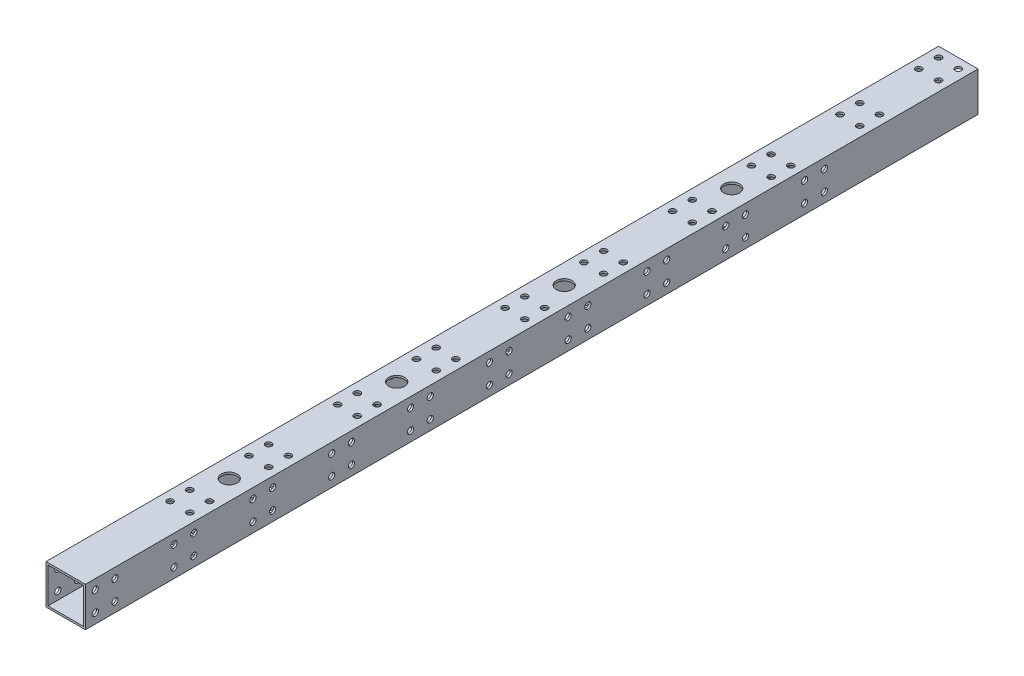
SolidWorks part; units mm, degrees
ref_plane "前视基准面" through (0, 0, 0) normal (0, 0, 1) x (1, 0, 0)
ref_plane "上视基准面" through (0, 0, 0) normal (0, 1, 0) x (1, 0, 0)
ref_plane "右视基准面" through (0, 0, 0) normal (1, 0, 0) x (0, 0, -1)
other "Configuration Table"
sketch "草图1" plane through (0, 0, 0) normal (0, 0, 1) x (1, 0, 0)
  line L1 (0, 0) -> (20, 0)
  line L2 (0, 0) -> (0, -20)
  line L3 (0, -20) -> (20, -20)
  line L4 (20, 0) -> (20, -20)
  dimension "D1" = 20
  dimension "D2" = 20
extrude "拉伸-薄壁1" add sketch "草图1" along normal blind 453 thin
sketch "草图2" plane through (20, 0, 0) normal (1, 0, 0) x (0, 0, -1)
  line L0 (-443, 0) -> (-443, -20) construction
  line L1 (-453, 0) -> (0, 0) construction
  line L2 (-453, -20) -> (0, -20) construction
  line L3 (-453, -20) -> (-453, 0) construction
  line L4 (-453, -10) -> (-443, -10) construction
  circle A0 centre (-448, -5) radius 1.575
  circle A1 centre (-448, -15) radius 1.575
  circle A2 centre (-438, -15) radius 1.575
  circle A3 centre (-438, -5) radius 1.575
  circle A4 centre (-408, -5) radius 1.575
  circle A5 centre (-398, -5) radius 1.575
  circle A6 centre (-398, -15) radius 1.575
  circle A7 centre (-408, -15) radius 1.575
  circle A8 centre (-368, -5) radius 1.575
  circle A9 centre (-358, -5) radius 1.575
  circle A10 centre (-358, -15) radius 1.575
  circle A11 centre (-368, -15) radius 1.575
  circle A12 centre (-328, -5) radius 1.575
  circle A13 centre (-318, -5) radius 1.575
  circle A14 centre (-318, -15) radius 1.575
  circle A15 centre (-328, -15) radius 1.575
  circle A16 centre (-288, -5) radius 1.575
  circle A17 centre (-278, -5) radius 1.575
  circle A18 centre (-278, -15) radius 1.575
  circle A19 centre (-288, -15) radius 1.575
  circle A20 centre (-248, -5) radius 1.575
  circle A21 centre (-238, -5) radius 1.575
  circle A22 centre (-238, -15) radius 1.575
  circle A23 centre (-248, -15) radius 1.575
  circle A24 centre (-208, -5) radius 1.575
  circle A25 centre (-198, -5) radius 1.575
  circle A26 centre (-198, -15) radius 1.575
  circle A27 centre (-208, -15) radius 1.575
  circle A28 centre (-168, -5) radius 1.575
  circle A29 centre (-158, -5) radius 1.575
  circle A30 centre (-158, -15) radius 1.575
  circle A31 centre (-168, -15) radius 1.575
  circle A32 centre (-128, -5) radius 1.575
  circle A33 centre (-118, -5) radius 1.575
  circle A34 centre (-118, -15) radius 1.575
  circle A35 centre (-128, -15) radius 1.575
  circle A36 centre (-88, -5) radius 1.575
  circle A37 centre (-78, -5) radius 1.575
  circle A38 centre (-78, -15) radius 1.575
  circle A39 centre (-88, -15) radius 1.575
  dimension "D1" = 3.15
  dimension "D2" = 10
  dimension "D3" = 5
  dimension "D4" = 5
  dimension "D5" = 40
extrude "切除-拉伸1" cut sketch "草图2" against normal through all
sketch "草图4" plane through (0, -20, 0) normal (0, -1, 0) x (1, 0, 0)
  line L0 (10, 0) -> (10, 10) construction
  line L1 (0, 0) -> (20, 0) construction
  line L2 (10, 10) -> (0, 10) construction
  line L3 (0, 453) -> (0, 0) construction
  line L4 (0, 30) -> (20, 30) construction
  line L5 (0, 453) -> (0, 0) construction
  line L6 (20, 453) -> (20, 0) construction
  line L7 (20, 0) -> (0, 0) construction
  line L8 (10, 50) -> (0, 50) construction
  line L9 (10, 60) -> (10, 50) construction
  circle A0 centre (5, 5) radius 1.575
  circle A1 centre (15, 5) radius 1.575
  circle A2 centre (15, 15) radius 1.575
  circle A3 centre (5, 15) radius 1.575
  circle A4 centre (5, 45) radius 1.575
  circle A5 centre (15, 45) radius 1.575
  circle A6 centre (15, 55) radius 1.575
  circle A7 centre (5, 55) radius 1.575
  circle A8 centre (5, 140) radius 1.575
  circle A9 centre (15, 140) radius 1.575
  circle A10 centre (5, 130) radius 1.575
  circle A11 centre (15, 130) radius 1.575
  circle A12 centre (5, 100) radius 1.575
  circle A13 centre (5, 90) radius 1.575
  circle A14 centre (15, 100) radius 1.575
  circle A15 centre (15, 90) radius 1.575
  circle A16 centre (5, 225) radius 1.575
  circle A17 centre (15, 225) radius 1.575
  circle A18 centre (5, 215) radius 1.575
  circle A19 centre (15, 215) radius 1.575
  circle A20 centre (5, 185) radius 1.575
  circle A21 centre (5, 175) radius 1.575
  circle A22 centre (15, 185) radius 1.575
  circle A23 centre (15, 175) radius 1.575
  circle A24 centre (5, 310) radius 1.575
  circle A25 centre (15, 310) radius 1.575
  circle A26 centre (5, 300) radius 1.575
  circle A27 centre (15, 300) radius 1.575
  circle A28 centre (5, 270) radius 1.575
  circle A29 centre (5, 260) radius 1.575
  circle A30 centre (15, 270) radius 1.575
  circle A31 centre (15, 260) radius 1.575
  circle A32 centre (5, 395) radius 1.575
  circle A33 centre (15, 395) radius 1.575
  circle A34 centre (5, 385) radius 1.575
  circle A35 centre (15, 385) radius 1.575
  circle A36 centre (5, 355) radius 1.575
  circle A37 centre (5, 345) radius 1.575
  circle A38 centre (15, 355) radius 1.575
  circle A39 centre (15, 345) radius 1.575
  circle A40 centre (10, 115) radius 4
  circle A41 centre (10, 200) radius 4
  circle A42 centre (10, 285) radius 4
  circle A43 centre (10, 370) radius 4
  dimension "D1" = 3.15
  dimension "D7" = 8
  dimension "D2" = 5
  dimension "D3" = 5
  dimension "D4" = 10
  dimension "D5" = 30
  dimension "D6" = 85
  dimension "D8" = 10
  dimension "D9" = 15
  dimension "D10" = 85
extrude "切除-拉伸2" cut sketch "草图4" against normal through all
